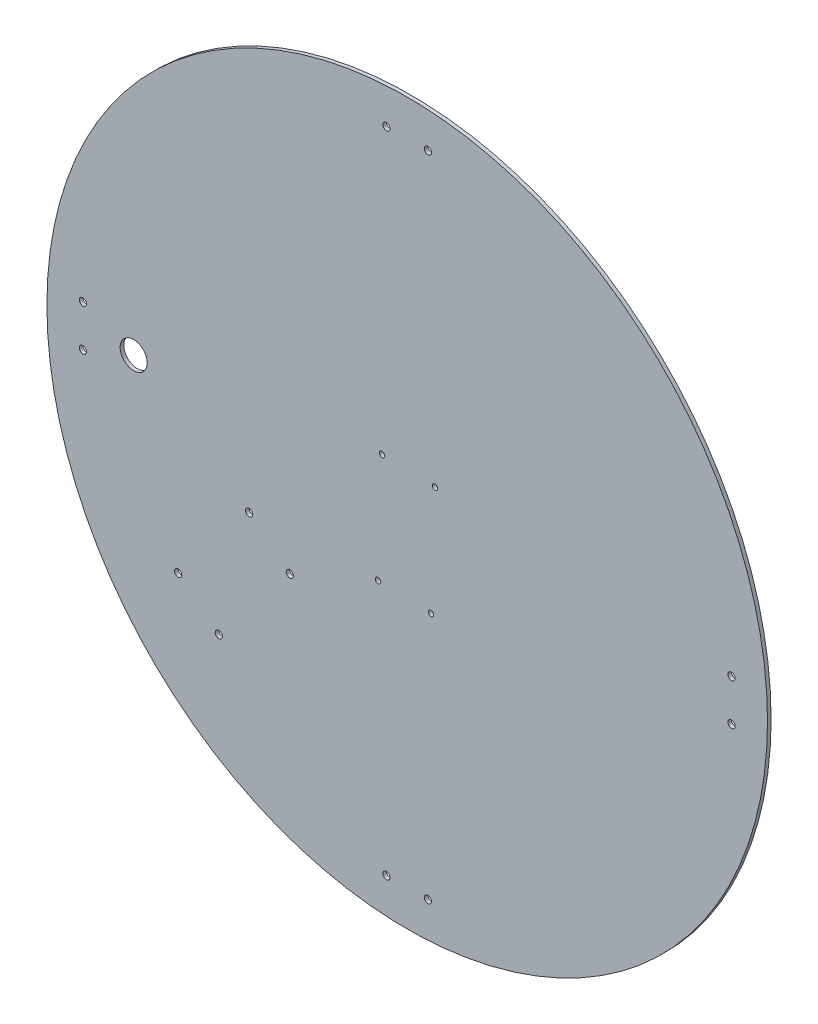
SolidWorks part; units mm, degrees
ref_plane "Front Plane" through (0, 0, 0) normal (0, 0, 1) x (1, 0, 0)
ref_plane "Top Plane" through (0, 0, 0) normal (0, 1, 0) x (1, 0, 0)
ref_plane "Right Plane" through (0, 0, 0) normal (1, 0, 0) x (0, 0, -1)
sketch "Sketch1" plane through (0, 0, 0) normal (0, 0, 1) x (1, 0, 0)
  circle A0 centre (0, 0) radius 200
  dimension "D1" = 400
extrude "Boss-Extrude1" add sketch "Sketch1" along normal blind 2
sketch "Sketch2" plane through (0, 0, 0) normal (0, 0, -1) x (-1, 0, 0)
  line L0 (0, 0) -> (0, 200) construction
  line L1 (-11.5, 180) -> (11.5, 180) construction
  circle A0 centre (0, 0) radius 200 construction
  circle A1 centre (11.5, 180) radius 2
  circle A2 centre (-11.5, 180) radius 2
  point P9 (0, 180)
  dimension "D2" = 4
  dimension "D1" = 23
  dimension "D3" = 180
extrude "Cut-Extrude1" cut sketch "Sketch2" against normal blind 13
pattern_circular "CirPattern1" count 4 over 360 about axis through (0, 0, 0) along (0, 0, 1) of "Cut-Extrude1"
sketch "Sketch5" plane through (0, 0, 0) normal (0, 0, -1) x (-1, 0, 0)
  circle A0 centre (151.8296, 0) radius 7.5
  circle A1 centre (-11.5, -180) radius 2 construction
  dimension "D1" = 15
  dimension "D2" = 151.8296
  dimension "D3" = 163.3296
extrude "Cut-Extrude3" cut sketch "Sketch5" against normal blind 2
sketch "Sketch7" plane through (0, 0, 0) normal (0, 0, -1) x (-1, 0, 0)
  circle A0 centre (127.1307, -92.4129) radius 2
  circle A1 centre (104.5659, -110.6291) radius 2
  circle A2 centre (65.1811, -61.8426) radius 2
  circle A3 centre (87.7459, -43.6263) radius 2
  dimension "D1" = 4
extrude "Cut-Extrude4" cut sketch "Sketch7" against normal blind 10
sketch "Sketch8" plane through (0, 0, 0) normal (0, 0, -1) x (-1, 0, 0)
  circle A0 centre (-15.4329, 20.1595) radius 1.5
  circle A1 centre (13.9482, 21.2138) radius 1.5
  circle A2 centre (-13.2166, -41.6007) radius 1.5
  circle A3 centre (16.1644, -40.5464) radius 1.5
  dimension "D1" = 3
extrude "Cut-Extrude5" cut sketch "Sketch8" against normal blind 10
